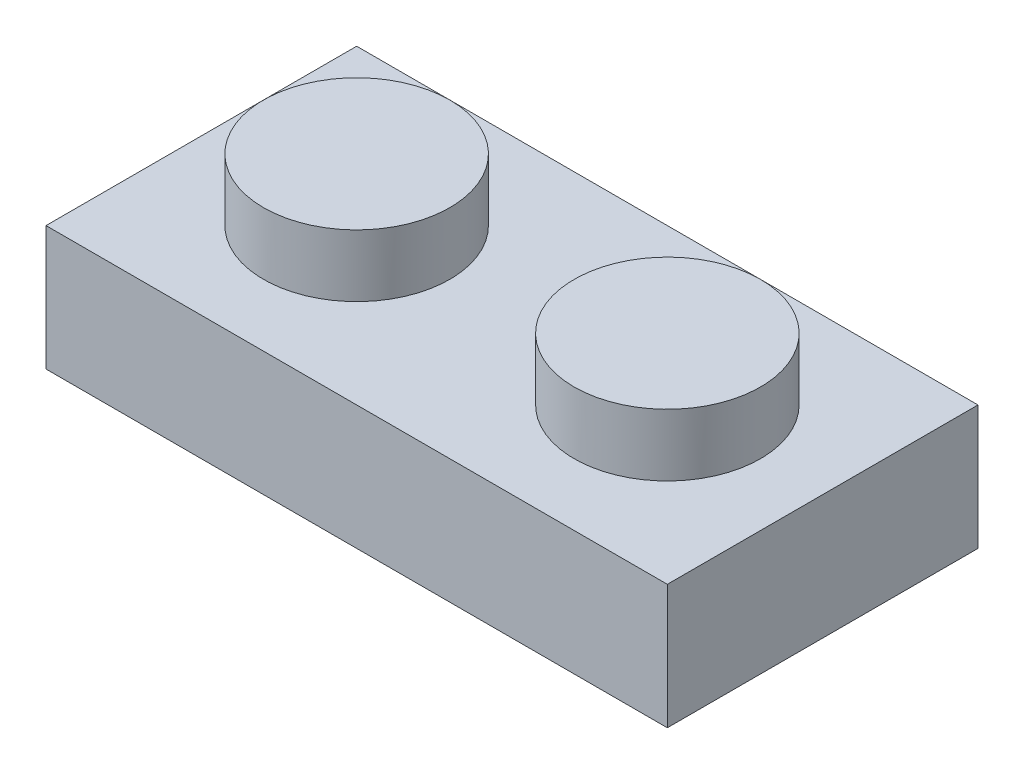
SolidWorks part; units mm, degrees
ref_plane "Front Plane" through (0, 0, 0) normal (0, 0, 1) x (1, 0, 0)
ref_plane "Top Plane" through (0, 0, 0) normal (0, 1, 0) x (1, 0, 0)
ref_plane "Right Plane" through (0, 0, 0) normal (1, 0, 0) x (0, 0, -1)
sketch "Sketch1" plane through (0, 0, 0) normal (0, 1, 0) x (1, 0, 0)
  line L1 (0, 0) -> (16, 0)
  line L2 (0, 0) -> (0, 8)
  line L3 (0, 8) -> (16, 8)
  line L4 (16, 0) -> (16, 8)
  dimension "D1" = 16
  dimension "D2" = 8
extrude "Boss-Extrude1" add sketch "Sketch1" along normal blind 3.2
sketch "Sketch2" plane through (0, 3.2, 0) normal (0, 1, 0) x (1, 0, 0)
  line L0 (8, 0) -> (8, 8) construction
  line L1 (0, 0) -> (16, 0) construction
  line L2 (16, 8) -> (0, 8) construction
  line L3 (16, 0) -> (16, 4) construction
  line L4 (16, 0) -> (16, 8) construction
  line L5 (16, 4) -> (12, 4) construction
  circle A0 centre (12, 4) radius 2.4
  dimension "D3" = 4.8
  dimension "D1" = 4
  dimension "D2" = 4
extrude "Boss-Extrude2" add sketch "Sketch2" along normal blind 1.6
pattern_linear "LPattern1" count 2 spacing 8 along (-1, 0, 0) count 4 spacing 8 along (0, 0, -1) of "Boss-Extrude2"
shell "Shell1" thickness 1.6
